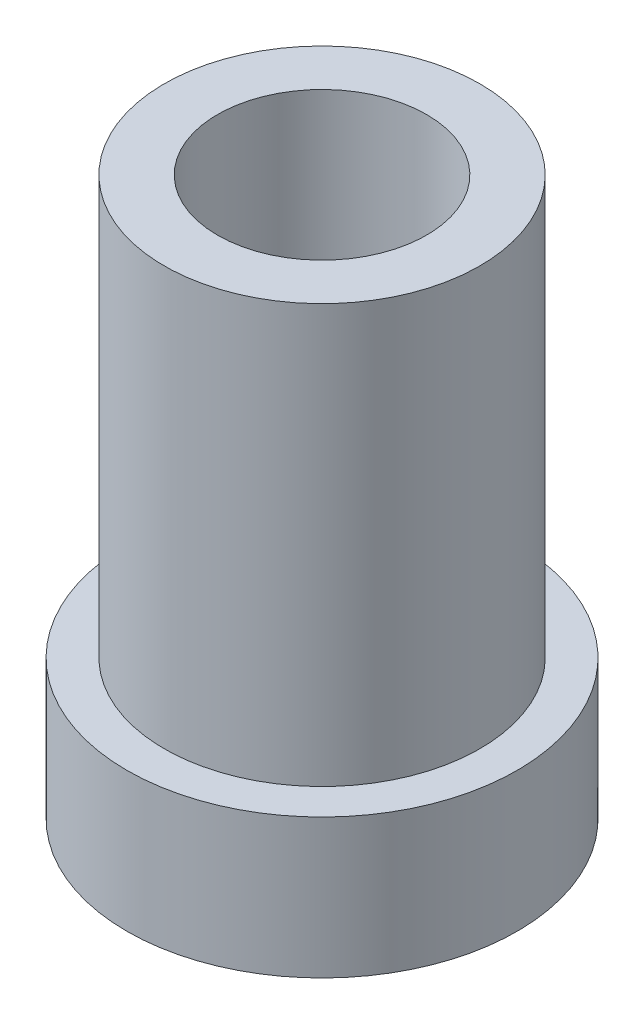
SolidWorks part; units mm, degrees
material "6061 Alloy"
ref_plane "Front Plane" through (0, 0, 0) normal (0, 0, 1) x (1, 0, 0)
ref_plane "Top Plane" through (0, 0, 0) normal (0, 1, 0) x (1, 0, 0)
ref_plane "Right Plane" through (0, 0, 0) normal (1, 0, 0) x (0, 0, -1)
sketch "Sketch1" plane through (0, 0, 0) normal (0, 1, 0) x (1, 0, 0)
  circle A0 centre (0, 0) radius 4.445
  dimension "D1" = 8.89
extrude "Boss-Extrude1" add sketch "Sketch1" along normal blind 3.175
sketch "Sketch2" plane through (0, 3.175, 0) normal (0, 1, 0) x (1, 0, 0)
  circle A1 centre (0, 0) radius 3.5941
  dimension "D2" = 7.1882
extrude "Boss-Extrude2" add sketch "Sketch2" along normal blind 9.525
sketch "Sketch3" plane through (0, 12.7, 0) normal (0, 1, 0) x (1, 0, 0)
  circle A0 centre (0, 0) radius 2.3813
  dimension "D1" = 4.7625
extrude "Cut-Extrude1" cut sketch "Sketch3" against normal up to surface (12.7 mm away) contours A0 up to face at (0, 0, 4.445)
